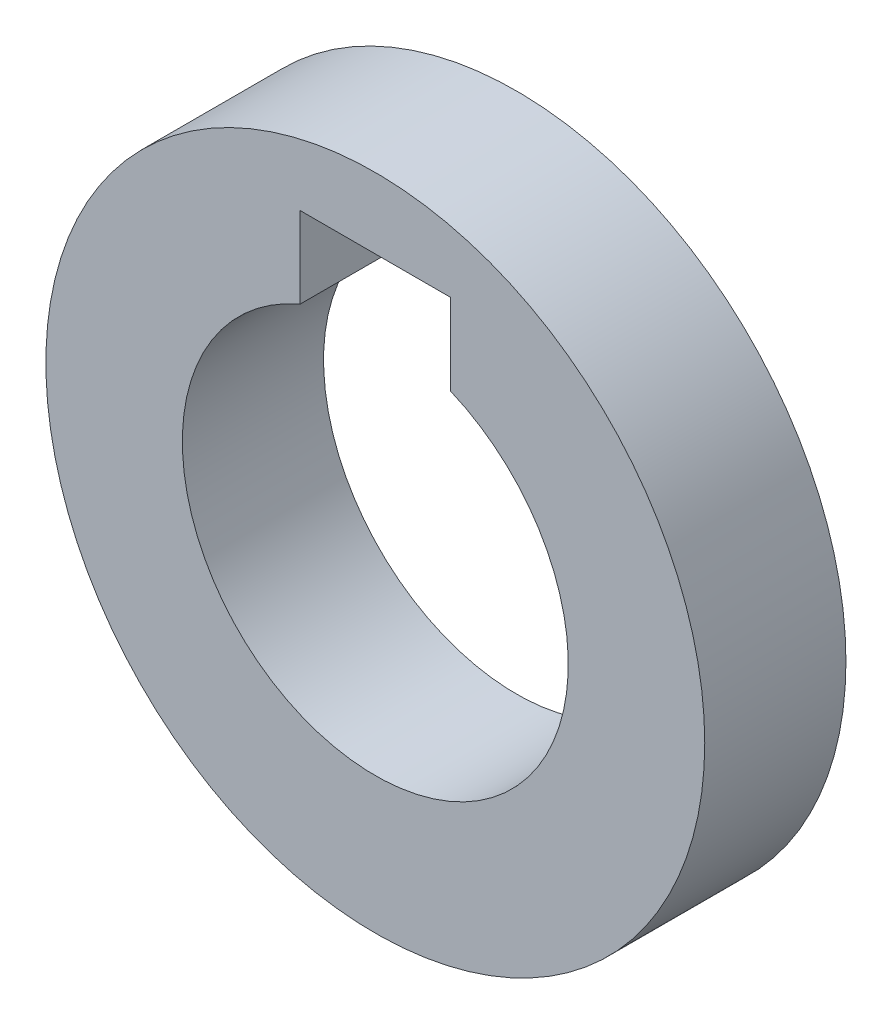
SolidWorks part; units mm, degrees
ref_plane "Front Plane" through (0, 0, 0) normal (0, 0, 1) x (1, 0, 0)
ref_plane "Top Plane" through (0, 0, 0) normal (0, 1, 0) x (1, 0, 0)
ref_plane "Right Plane" through (0, 0, 0) normal (1, 0, 0) x (0, 0, -1)
sketch "Sketch1" plane through (0, 0, 0) normal (0, 0, 1) x (1, 0, 0)
  line L0 (-1.6, 3.7749) -> (-1.6, 5.5)
  line L1 (-1.6, 5.5) -> (1.6, 5.5)
  line L2 (1.6, 5.5) -> (1.6, 3.7749)
  line L3 (0, 0) -> (0, 7) construction
  circle A0 centre (0, 0) radius 4.1 construction
  circle A1 centre (0, 0) radius 7
  arc A2 (-1.6, 3.7749) -> (1.6, 3.7749) centre (0, 0) ccw
  dimension "D1" = 8.2
  dimension "D2" = 14
  dimension "D3" = 3.2
  dimension "D4" = 5.5
extrude "Boss-Extrude1" add sketch "Sketch1" along normal blind 3
